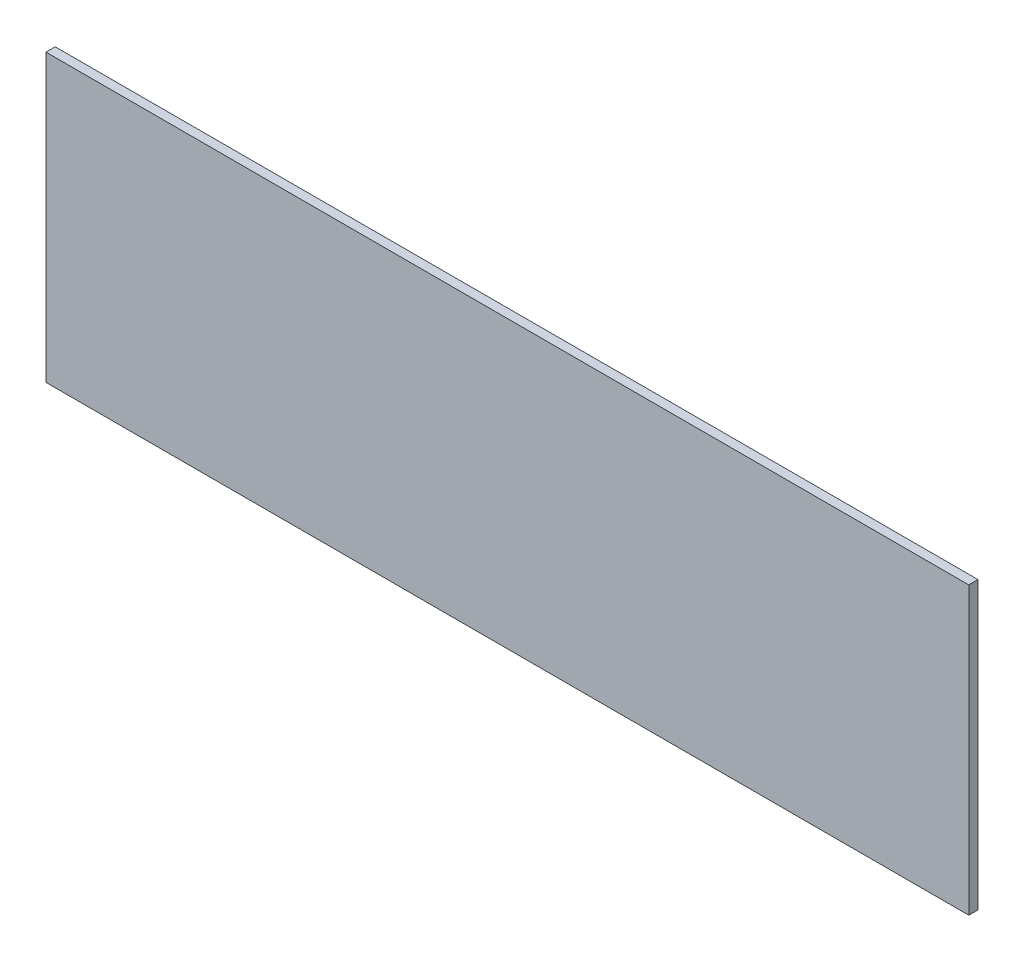
SolidWorks part; units mm, degrees
ref_plane "Front Plane" through (0, 0, 0) normal (0, 0, 1) x (1, 0, 0)
ref_plane "Top Plane" through (0, 0, 0) normal (0, 1, 0) x (1, 0, 0)
ref_plane "Right Plane" through (0, 0, 0) normal (1, 0, 0) x (0, 0, -1)
sketch "Sketch1" plane through (0, 0, 0) normal (0, 0, 1) x (1, 0, 0)
  line L0 (-122, 0) -> (-122, -3)
  line L1 (-122, -3) -> (-122, -93)
  line L2 (-122, -93) -> (178, -93)
  line L3 (178, -93) -> (178, -3)
  line L4 (178, -3) -> (178, 0)
  line L5 (178, 0) -> (-122, 0)
extrude "Boss-Extrude1" add sketch "Sketch1" along normal blind 3
